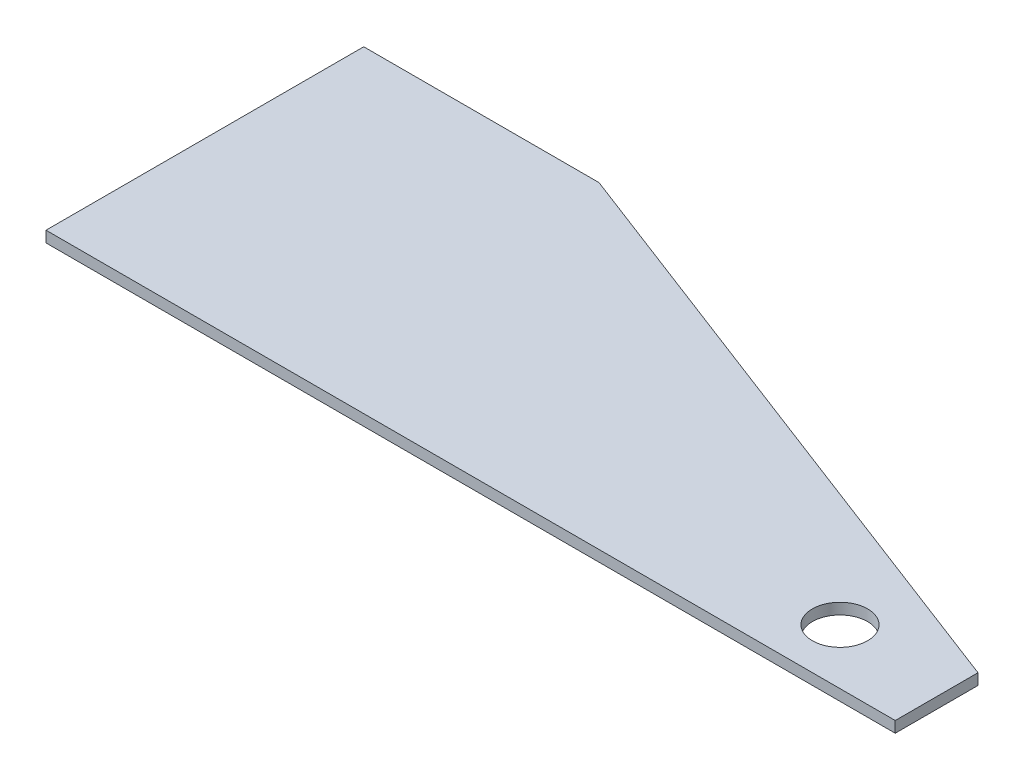
SolidWorks part; units mm, degrees
ref_plane "Front Plane" through (0, 0, 0) normal (0, 0, 1) x (1, 0, 0)
ref_plane "Top Plane" through (0, 0, 0) normal (0, 1, 0) x (1, 0, 0)
ref_plane "Right Plane" through (0, 0, 0) normal (1, 0, 0) x (0, 0, -1)
sketch "Sketch1" plane through (0, 0, 0) normal (0, 1, 0) x (1, 0, 0)
  line L0 (0, 0) -> (42.5925, 0)
  line L1 (42.5925, 0) -> (153.7152, -42.5298)
  line L2 (153.7152, -42.5298) -> (153.7152, -57.5087)
  line L3 (153.7152, -57.5087) -> (0, -57.5087)
  line L4 (0, -57.5087) -> (0, 0)
extrude "Boss-Extrude1" add sketch "Sketch1" along normal blind 2
sketch "Sketch2" plane through (0, 2, 0) normal (0, 1, 0) x (1, 0, 0)
  line L0 (153.7152, -57.5087) -> (153.7152, -42.5298) construction
  line L1 (0, -57.5087) -> (153.7152, -57.5087) construction
  circle A0 centre (133.7152, -47.5087) radius 5
  dimension "D2" = 10
  dimension "D1" = 20
  dimension "D3" = 10
extrude "Cut-Extrude1" cut sketch "Sketch2" against normal through all
